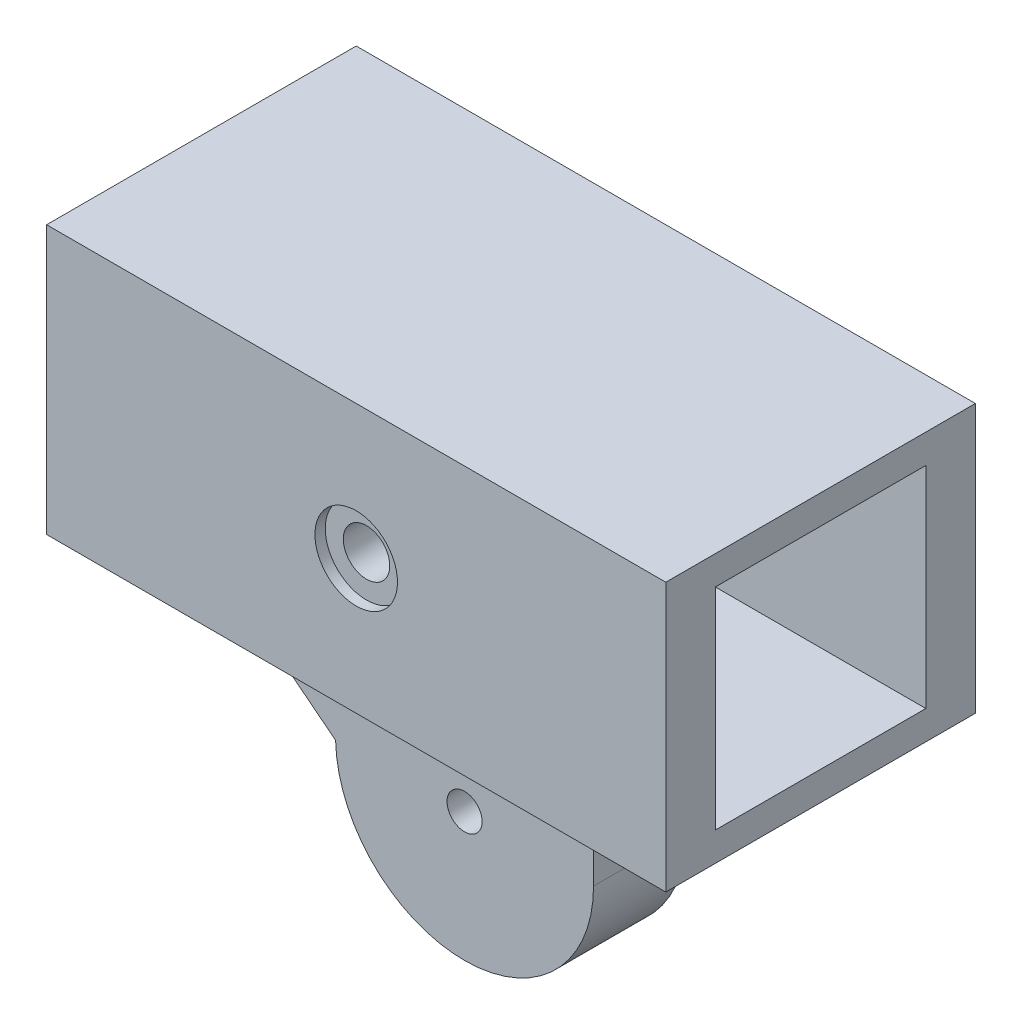
SolidWorks part; units mm, degrees
ref_plane "Plan de face" through (0, 0, 0) normal (0, 0, 1) x (1, 0, 0)
ref_plane "Plan de dessus" through (0, 0, 0) normal (0, 1, 0) x (1, 0, 0)
ref_plane "Plan de droite" through (0, 0, 0) normal (1, 0, 0) x (0, 0, -1)
sketch "Esquisse1" plane through (0, 0, 0) normal (1, 0, 0) x (0, 0, -1)
  line L1 (-15, 26) -> (15, 26)
  line L2 (-15, 26) -> (-15, 0)
  line L3 (-15, 0) -> (15, 0)
  line L4 (15, 26) -> (15, 0)
  dimension "D1" = 30
  dimension "D2" = 26
extrude "Boss.-Extru.1" add sketch "Esquisse1" along normal blind 60
sketch "Esquisse4" plane through (0, 0, 0) normal (0, 0, 1) x (1, 0, 0)
  line L0 (17.5, 0) -> (17.5, -13.5)
  line L1 (60, 0) -> (0, 0) construction
  line L2 (42.5, -13.5) -> (42.5, 0)
  line L3 (42.5, 0) -> (17.5, 0)
  arc A0 (17.5, -13.5) -> (42.5, -13.5) centre (30, -13.5) ccw
  point P6 (30, 0)
  point P8 (30, 0)
  dimension "D1" = 25
extrude "Boss.-Extru.2" add sketch "Esquisse4" along normal mid plane 9
sketch "Esquisse3" plane through (0, 0, 0) normal (-1, 0, 0) x (0, 0, 1)
  line L0 (-15, 26) -> (15, 0) construction
  line L1 (15, 26) -> (-15, 0) construction
  line L2 (-10.2, 23.2) -> (10.2, 23.2)
  line L3 (-10.2, 23.2) -> (-10.2, 2.8)
  line L4 (-10.2, 2.8) -> (10.2, 2.8)
  line L5 (10.2, 23.2) -> (10.2, 2.8)
  line L6 (-10.2, 23.2) -> (10.2, 2.8) construction
  line L7 (-10.2, 2.8) -> (10.2, 23.2) construction
  point P0 (0, 13)
  point P14 (0, 13)
  dimension "D1" = 20.4
  dimension "D2" = 20.4
extrude "Enlèv. mat.-Extru.1" cut sketch "Esquisse3" against normal blind 60
hole_wizard "Dégagement M31" positions "Esquisse5" profile "Esquisse6" hole size "M3" standard "ISO" end condition through all
sketch "Esquisse5" plane through (0, 0, 4.5) normal (0, 0, 1) x (1, 0, 0)
  point P0 (30, -13.5)
sketch "Esquisse6" plane through (30, -13.5, 4.5) normal (1, 0, 0) x (0, -1, 0)
  line L0 (0, 0) -> (0, 19.5)
  line L1 (0, 19.5) -> (1.7, 19.5)
  line L2 (1.7, 19.5) -> (1.7, 0)
  line L5 (1.7, 0) -> (0, 0)
  line L11 (0, -6.35) -> (0, 107.95) construction
  dimension "Diamètre du perçage jusqu'au prochain" = 3.4
  dimension "Profondeur du perçage jusqu'au prochain" = 19.5
sketch "Esquisse7" plane through (0, 0, 0) normal (0, 0, 1) x (1, 0, 0)
  line L0 (0, 0) -> (17.5, -13.7672)
  line L1 (60, 0) -> (0, 0) construction
rib "Nervure3" sketch "Esquisse7" sketch "Esquisse7" thickness 9 extrusion direction parallel to sketch draft on no parameters "D1"=9
hole_wizard "Chambrage pour vis à tête hexagonale M41" positions "Esquisse8" profile "Esquisse9" counterbore size "M4" standard "ISO"
sketch "Esquisse8" plane through (0, 0, 15) normal (0, 0, 1) x (1, 0, 0)
  point P0 (30, 13)
sketch "Esquisse9" plane through (30, 13, 15) normal (1, 0, 0) x (0, -1, 0)
  line L0 (0, 0) -> (0, 4.8)
  line L1 (0, 4.8) -> (2.25, 4.8)
  line L3 (2.25, 4.8) -> (2.25, 1)
  line L4 (2.25, 1) -> (4, 1)
  line L5 (4, 1) -> (4, 0)
  line L7 (4, 0) -> (0, 0)
  line L11 (0, -6.35) -> (0, 107.95) construction
  dimension "Diamètre du perçage jusqu'au prochain" = 4.5
  dimension "Profondeur du perçage jusqu'au prochain" = 4.8
  dimension "Diamètre du chambrage" = 8
  dimension "Profondeur du chambrage" = 1
mirror "Symétrie1" about plane through (0, 0, 0) normal (0, 0, 1) of "Chambrage pour vis à tête hexagonale M41"
